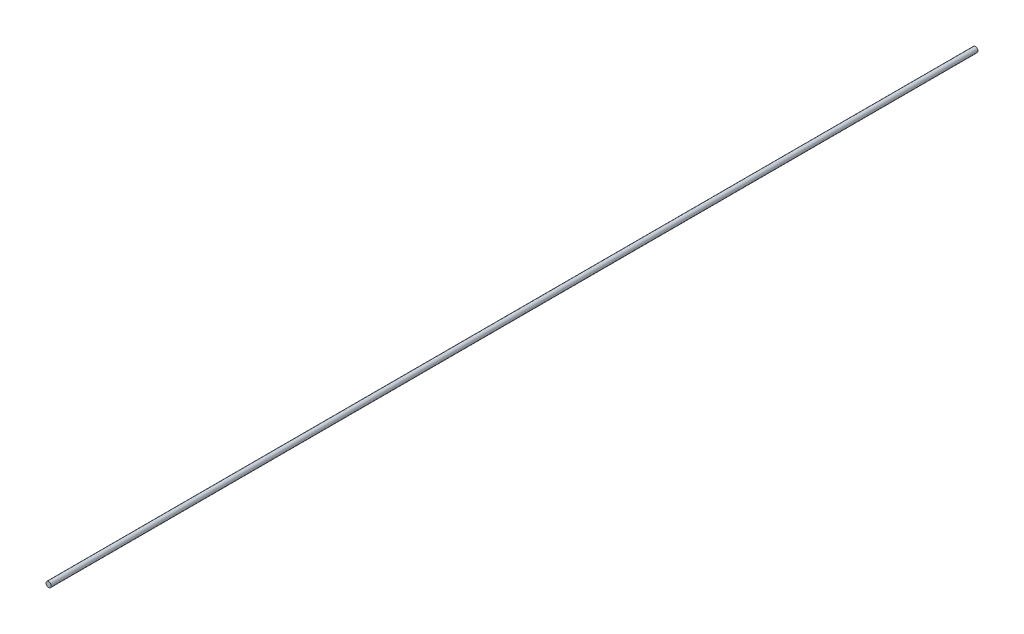
SolidWorks part; units mm, degrees
material "7075-T6 (SN)"
ref_plane "Front Plane" through (0, 0, 0) normal (0, 0, 1) x (1, 0, 0)
ref_plane "Top Plane" through (0, 0, 0) normal (0, 1, 0) x (1, 0, 0)
ref_plane "Right Plane" through (0, 0, 0) normal (1, 0, 0) x (0, 0, -1)
sketch "Sketch1" plane through (0, 0, 0) normal (0, 0, 1) x (1, 0, 0)
  circle A0 centre (0, 0) radius 12.7
  dimension "D1" = 25.4
extrude "Boss-Extrude2" add sketch "Sketch1" along normal blind 4488.5505 contours A0
equation "\"E\"= 10 * ( 10 ^ 6 )"
equation "\"A\"= 0.7853981634"
equation "\"D\"= 0.009"
equation "\"P\"= 400"
equation "\"Lm\"= ( \"D\" * \"A\" * \"E\" ) / \"P\""
equation "\"D1@Boss-Extrude2\"=\"Lm\""
